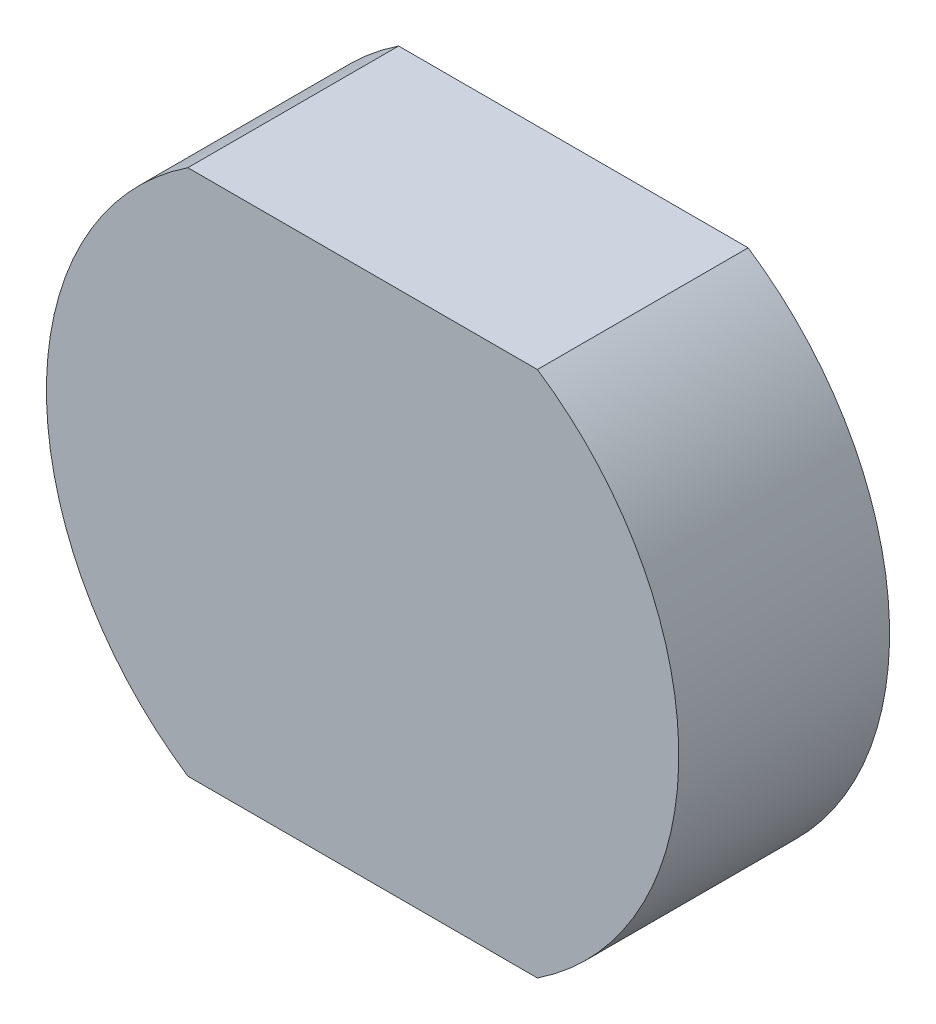
SolidWorks part; units mm, degrees
ref_plane "Спереди" through (0, 0, 0) normal (0, 0, 1) x (1, 0, 0)
ref_plane "Сверху" through (0, 0, 0) normal (0, 1, 0) x (1, 0, 0)
ref_plane "Справа" through (0, 0, 0) normal (1, 0, 0) x (0, 0, -1)
sketch "Эскиз1" plane through (0, 0, 0) normal (0, 0, 1) x (1, 0, 0)
  line L0 (-8.2916, 12.5) -> (8.2916, 12.5)
  line L1 (-8.2916, -12.5) -> (8.2916, -12.5)
  arc A0 (-8.2916, 12.5) -> (-8.2916, -12.5) centre (0, 0) ccw
  arc A1 (8.2916, -12.5) -> (8.2916, 12.5) centre (0, 0) ccw
  dimension "D1" = 15
  dimension "D2" = 12.5
  dimension "D3" = 12.5
extrude "Бобышка-Вытянуть1" add sketch "Эскиз1" along normal blind 10
